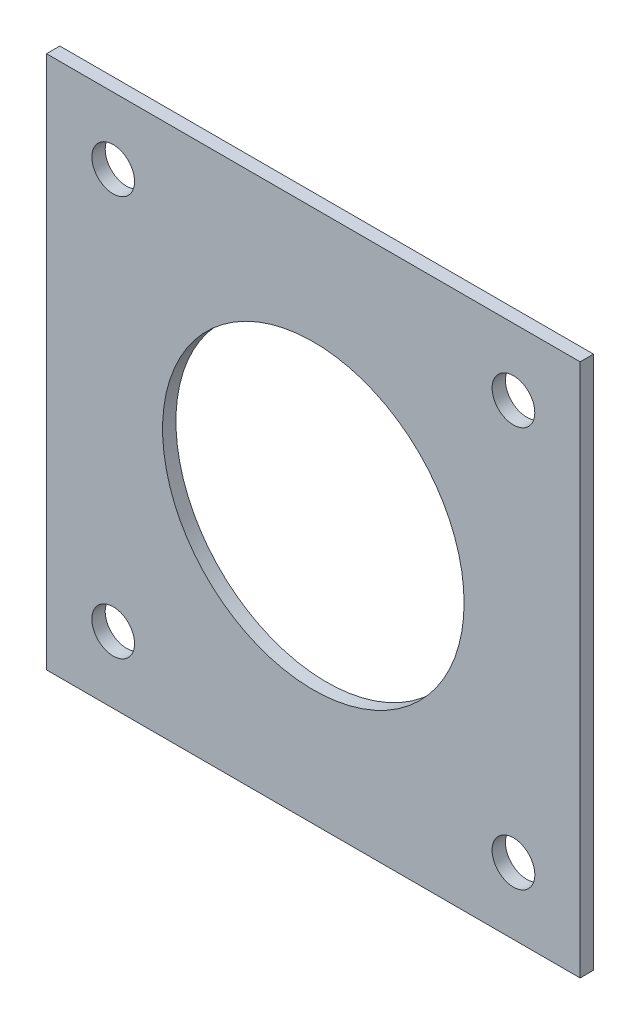
SolidWorks part; units mm, degrees
ref_plane "Front Plane" through (0, 0, 0) normal (0, 0, 1) x (1, 0, 0)
ref_plane "Top Plane" through (0, 0, 0) normal (0, 1, 0) x (1, 0, 0)
ref_plane "Right Plane" through (0, 0, 0) normal (1, 0, 0) x (0, 0, -1)
sketch "Sketch1" plane through (0, 0, 0) normal (0, 0, 1) x (1, 0, 0)
  line L0 (0, 14.351) -> (0, -14.351) construction
  line L1 (-25.4, -25.4) -> (25.4, -25.4)
  line L2 (-25.4, -25.4) -> (-25.4, 25.4)
  line L3 (-25.4, 25.4) -> (25.4, 25.4)
  line L4 (25.4, -25.4) -> (25.4, 25.4)
  line L5 (-25.4, -25.4) -> (25.4, 25.4) construction
  line L6 (-25.4, 25.4) -> (25.4, -25.4) construction
  line L7 (-14.351, 0) -> (14.351, 0) construction
  circle A0 centre (0, 0) radius 14.351
  circle A1 centre (19.05, 19.05) radius 2.032
  circle A2 centre (-19.05, 19.05) radius 2.032
  circle A3 centre (19.05, -19.05) radius 2.032
  circle A4 centre (-19.05, -19.05) radius 2.032
  point P0 (0, 0)
  dimension "D1" = 28.702
  dimension "D6" = 4.064
  dimension "D2" = 50.8
  dimension "D3" = 50.8
  dimension "D4" = 6.35
  dimension "D5" = 6.35
extrude "Boss-Extrude1" add sketch "Sketch1" along normal mid plane 1.27
